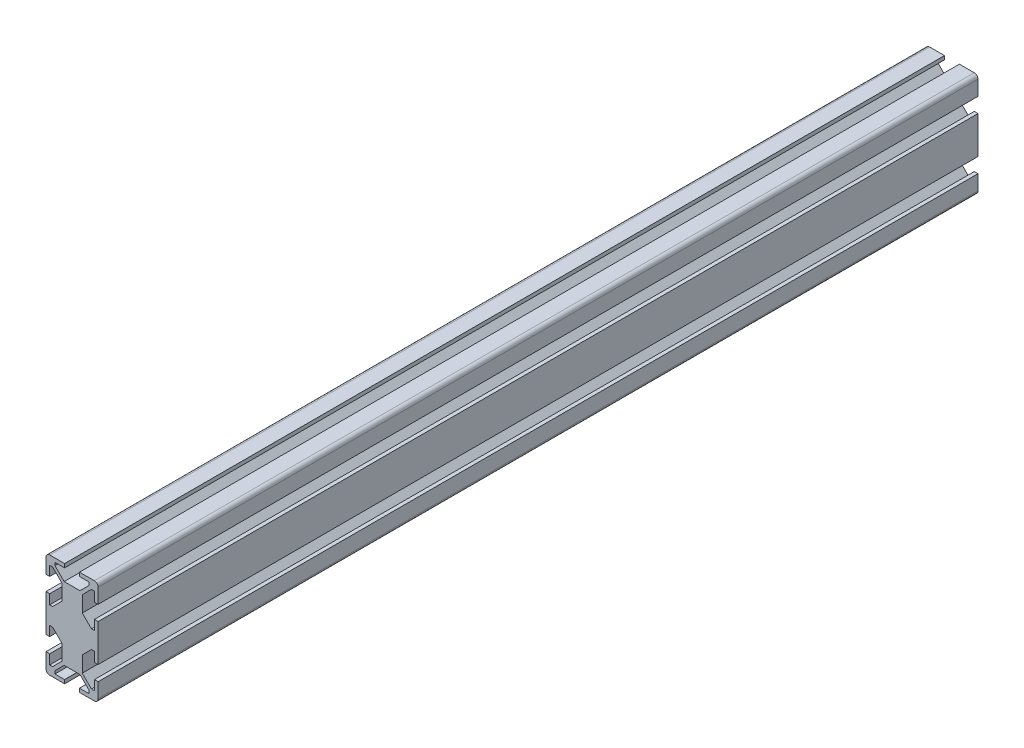
SolidWorks part; units mm, degrees
material "6061 Aluminum Alloy"
ref_plane "Front Plane" through (0, 0, 0) normal (0, 0, 1) x (1, 0, 0)
ref_plane "Top Plane" through (0, 0, 0) normal (0, 1, 0) x (1, 0, 0)
ref_plane "Right Plane" through (0, 0, 0) normal (1, 0, 0) x (0, 0, -1)
sketch "Sketch1" plane through (0, 0, 0) normal (0, 0, 1) x (1, 0, 0)
  line L0 (-51.9455, 19.536) -> (-51.9455, -0.464)
  line L1 (-51.9455, -0.464) -> (-49.9455, -0.464)
  line L2 (-49.9455, -0.464) -> (-49.9455, 4.7413)
  line L3 (-49.9455, 4.7413) -> (-48.3862, 4.7413)
  line L4 (-48.3862, 4.7413) -> (-43.4455, -0.1995)
  line L5 (-43.4455, -0.1995) -> (-43.4455, -8.7179)
  line L6 (-43.4455, -8.7179) -> (-48.3862, -13.6587)
  line L7 (-48.3862, -13.6587) -> (-49.9455, -13.6587)
  line L8 (-49.9455, -13.6587) -> (-49.9455, -8.4587)
  line L9 (-49.9455, -8.4587) -> (-51.9455, -8.4587)
  line L10 (-51.9455, -8.4587) -> (-51.9455, -16.4587)
  line L11 (-49.9455, -18.4587) -> (-41.9455, -18.4587)
  line L12 (-41.9455, -18.4587) -> (-41.9455, -16.4587)
  line L13 (-41.9455, -16.4587) -> (-47.1455, -16.4587)
  line L14 (-47.1455, -16.4587) -> (-47.1455, -14.8995)
  line L15 (-47.1455, -14.8995) -> (-42.2047, -9.9587)
  line L16 (-42.2047, -9.9587) -> (-33.6862, -9.9587)
  line L17 (-33.6862, -9.9587) -> (-28.7455, -14.8995)
  line L18 (-28.7455, -14.8995) -> (-28.7455, -16.4587)
  line L19 (-28.7455, -16.4587) -> (-33.9455, -16.4587)
  line L20 (-33.9455, -16.4587) -> (-33.9455, -18.4587)
  line L21 (-33.9455, -18.4587) -> (-25.9455, -18.4587)
  line L22 (-23.9455, -16.4587) -> (-23.9455, -8.4587)
  line L23 (-23.9455, -8.4587) -> (-25.9455, -8.4587)
  line L24 (-25.9455, -8.4587) -> (-25.9455, -13.6587)
  line L25 (-25.9455, -13.6587) -> (-27.5047, -13.6587)
  line L26 (-27.5047, -13.6587) -> (-32.4455, -8.7179)
  line L27 (-32.4455, -8.7179) -> (-32.4455, -0.1995)
  line L28 (-32.4455, -0.1995) -> (-27.5047, 4.7413)
  line L29 (-27.5047, 4.7413) -> (-25.9455, 4.7413)
  line L30 (-25.9455, 4.7413) -> (-25.9455, -0.464)
  line L31 (-25.9455, -0.464) -> (-23.9455, -0.464)
  line L32 (-23.9455, -0.464) -> (-23.9455, 19.5413)
  line L33 (-23.9455, 19.5413) -> (-25.9455, 19.5413)
  line L34 (-25.9455, 19.5413) -> (-25.9455, 14.3413)
  line L35 (-25.9455, 14.3413) -> (-27.5047, 14.3413)
  line L36 (-27.5047, 14.3413) -> (-32.4455, 19.2821)
  line L37 (-32.4455, 19.2821) -> (-32.4455, 27.8005)
  line L38 (-32.4455, 27.8005) -> (-27.5047, 32.7413)
  line L39 (-27.5047, 32.7413) -> (-25.9455, 32.7413)
  line L40 (-25.9455, 32.7413) -> (-25.9455, 27.5413)
  line L41 (-25.9455, 27.5413) -> (-23.9455, 27.5413)
  line L42 (-23.9455, 27.5413) -> (-23.9455, 35.5413)
  line L43 (-25.9455, 37.5413) -> (-33.9455, 37.5413)
  line L44 (-33.9455, 37.5413) -> (-33.9455, 35.5413)
  line L45 (-33.9455, 35.5413) -> (-28.7455, 35.5413)
  line L46 (-28.7455, 35.5413) -> (-28.7455, 33.9821)
  line L47 (-28.7455, 33.9821) -> (-33.6862, 29.0413)
  line L48 (-33.6862, 29.0413) -> (-42.2047, 29.0413)
  line L49 (-42.2047, 29.0413) -> (-47.1455, 33.9821)
  line L50 (-47.1455, 33.9821) -> (-47.1455, 35.5413)
  line L51 (-47.1455, 35.5413) -> (-41.9455, 35.5413)
  line L52 (-41.9455, 35.5413) -> (-41.9455, 37.5413)
  line L53 (-41.9455, 37.5413) -> (-49.9455, 37.5413)
  line L54 (-51.9455, 35.5413) -> (-51.9455, 27.5413)
  line L55 (-51.9455, 27.5413) -> (-49.9455, 27.5413)
  line L56 (-49.9455, 27.5413) -> (-49.9455, 32.736)
  line L57 (-49.9455, 32.736) -> (-48.3721, 32.736)
  line L58 (-48.3721, 32.736) -> (-43.4313, 27.7953)
  line L59 (-43.4313, 27.7953) -> (-43.4313, 19.2768)
  line L60 (-43.4313, 19.2768) -> (-48.3721, 14.336)
  line L61 (-48.3721, 14.336) -> (-49.9313, 14.336)
  line L62 (-49.9313, 14.336) -> (-49.9313, 19.536)
  line L63 (-49.9313, 19.536) -> (-51.9455, 19.536)
  line L64 (-33.6862, 18.0413) -> (-42.2047, 18.0413)
  line L65 (-42.2047, 18.0413) -> (-47.1455, 13.1005)
  line L66 (-47.1455, 13.1005) -> (-47.1455, 5.9821)
  line L67 (-47.1455, 5.9821) -> (-42.2047, 1.0413)
  line L68 (-42.2047, 1.0413) -> (-33.6862, 1.0413)
  line L69 (-33.6862, 1.0413) -> (-28.7455, 5.9821)
  line L70 (-28.7455, 5.9821) -> (-28.7455, 13.1005)
  line L71 (-28.7455, 13.1005) -> (-33.6862, 18.0413)
  arc A0 (-51.9455, -16.4587) -> (-49.9455, -18.4587) centre (-49.9455, -16.4587) ccw
  arc A1 (-25.9455, -18.4587) -> (-23.9455, -16.4587) centre (-25.9455, -16.4587) ccw
  arc A2 (-23.9455, 35.5413) -> (-25.9455, 37.5413) centre (-25.9455, 35.5413) ccw
  arc A3 (-49.9455, 37.5413) -> (-51.9455, 35.5413) centre (-49.9455, 35.5413) ccw
  circle A4 centre (-37.9455, -4.4587) radius 3.25
  circle A5 centre (-37.9455, 23.5413) radius 3.25
extrude "Extrusion2" add sketch "Sketch1" along normal up to vertex (161.5 mm away) and the other way up to vertex (161.5 mm away) contours L53 A3 L54 L55 L56 L57 L58 L59 L60 L61 L62 L63 L0 L1 L2 L3 L4 L5 L6 L7 L8 L9 L10 A0 L11 L12 L13 L14 L15 L16 L17 L18 L19 L20 L21 A1 L22 L23 L24 L25 L26 L27 L28 L29 L30 L31 L32 L33 L34 L35 L36
hole_wizard "Ø4.7 (4.7) Diameter Hole1" positions "Sketch3" profile "Sketch4" hole size "Ø4.7" standard "Macron Ansi Metric" end condition through all
sketch "Sketch3" plane through (-23.9455, 0, 0) normal (1, 0, 0) x (0, 0, -1)
  line L0 (-161.5, -0.464) -> (-161.5, 19.5413) construction
  line L1 (-161.5, 37.5413) -> (161.5, 37.5413) construction
  point P0 (-140.5, 23.5413)
  point P1 (140.5, 23.5413)
  dimension "D1" = 21
  dimension "D2" = 14
  dimension "D3" = 21
sketch "Sketch4" plane through (-23.9455, 23.5413, 140.5) normal (0, 1, 0) x (0, 0, -1)
  line L0 (0, 0) -> (0, 28)
  line L1 (0, 28) -> (2.375, 28)
  line L2 (2.375, 28) -> (2.375, 0)
  line L5 (2.375, 0) -> (0, 0)
  line L11 (0, -6.35) -> (0, 107.95) construction
  dimension "Thru Hole Dia." = 4.75
  dimension "Thru Hole Depth" = 28
sketch "Sketch5" plane through (0, 0, 161.5) normal (0, 0, 1) x (1, 0, 0)
  line L64 (-41.9455, 37.5413) -> (-49.9455, 37.5413)
  line L65 (-51.9455, 35.5413) -> (-51.9455, 27.5413)
  line L66 (-51.9455, 27.5413) -> (-49.9455, 27.5413)
  line L67 (-49.9455, 27.5413) -> (-49.9455, 32.736)
  line L68 (-49.9455, 32.736) -> (-48.3721, 32.736)
  line L69 (-48.3721, 32.736) -> (-43.4313, 27.7953)
  line L70 (-43.4313, 27.7953) -> (-43.4313, 19.2768)
  line L71 (-43.4313, 19.2768) -> (-48.3721, 14.336)
  line L72 (-48.3721, 14.336) -> (-49.9313, 14.336)
  line L73 (-49.9313, 14.336) -> (-49.9313, 19.536)
  line L74 (-49.9313, 19.536) -> (-51.9455, 19.536)
  line L75 (-51.9455, 19.536) -> (-51.9455, -0.464)
  line L76 (-51.9455, -0.464) -> (-49.9455, -0.464)
  line L77 (-49.9455, -0.464) -> (-49.9455, 4.7413)
  line L78 (-49.9455, 4.7413) -> (-48.3862, 4.7413)
  line L79 (-48.3862, 4.7413) -> (-43.4455, -0.1995)
  line L80 (-43.4455, -0.1995) -> (-43.4455, -8.7179)
  line L81 (-43.4455, -8.7179) -> (-48.3862, -13.6587)
  line L82 (-48.3862, -13.6587) -> (-49.9455, -13.6587)
  line L83 (-49.9455, -13.6587) -> (-49.9455, -8.4587)
  line L84 (-49.9455, -8.4587) -> (-51.9455, -8.4587)
  line L85 (-51.9455, -8.4587) -> (-51.9455, -16.4587)
  line L86 (-49.9455, -18.4587) -> (-41.9455, -18.4587)
  line L87 (-41.9455, -18.4587) -> (-41.9455, -16.4587)
  line L88 (-41.9455, -16.4587) -> (-47.1455, -16.4587)
  line L89 (-47.1455, -16.4587) -> (-47.1455, -14.8995)
  line L90 (-47.1455, -14.8995) -> (-42.2047, -9.9587)
  line L91 (-42.2047, -9.9587) -> (-33.6862, -9.9587)
  line L92 (-33.6862, -9.9587) -> (-28.7455, -14.8995)
  line L93 (-28.7455, -14.8995) -> (-28.7455, -16.4587)
  line L94 (-28.7455, -16.4587) -> (-33.9455, -16.4587)
  line L95 (-33.9455, -16.4587) -> (-33.9455, -18.4587)
  line L96 (-33.9455, -18.4587) -> (-25.9455, -18.4587)
  line L97 (-23.9455, -16.4587) -> (-23.9455, -8.4587)
  line L98 (-23.9455, -8.4587) -> (-25.9455, -8.4587)
  line L99 (-25.9455, -8.4587) -> (-25.9455, -13.6587)
  line L100 (-25.9455, -13.6587) -> (-27.5047, -13.6587)
  line L101 (-27.5047, -13.6587) -> (-32.4455, -8.7179)
  line L102 (-32.4455, -8.7179) -> (-32.4455, -0.1995)
  line L103 (-32.4455, -0.1995) -> (-27.5047, 4.7413)
  line L104 (-27.5047, 4.7413) -> (-25.9455, 4.7413)
  line L105 (-25.9455, 4.7413) -> (-25.9455, -0.464)
  line L106 (-25.9455, -0.464) -> (-23.9455, -0.464)
  line L107 (-23.9455, -0.464) -> (-23.9455, 19.5413)
  line L108 (-23.9455, 19.5413) -> (-25.9455, 19.5413)
  line L109 (-25.9455, 19.5413) -> (-25.9455, 14.3413)
  line L110 (-25.9455, 14.3413) -> (-27.5047, 14.3413)
  line L111 (-27.5047, 14.3413) -> (-32.4455, 19.2821)
  line L112 (-32.4455, 19.2821) -> (-32.4455, 27.8005)
  line L113 (-32.4455, 27.8005) -> (-27.5047, 32.7413)
  line L114 (-27.5047, 32.7413) -> (-25.9455, 32.7413)
  line L115 (-25.9455, 32.7413) -> (-25.9455, 27.5413)
  line L116 (-25.9455, 27.5413) -> (-23.9455, 27.5413)
  line L117 (-23.9455, 27.5413) -> (-23.9455, 35.5413)
  line L118 (-25.9455, 37.5413) -> (-33.9455, 37.5413)
  line L119 (-33.9455, 37.5413) -> (-33.9455, 35.5413)
  line L120 (-33.9455, 35.5413) -> (-28.7455, 35.5413)
  line L121 (-28.7455, 35.5413) -> (-28.7455, 33.9821)
  line L122 (-28.7455, 33.9821) -> (-33.6862, 29.0413)
  line L123 (-33.6862, 29.0413) -> (-42.2047, 29.0413)
  line L124 (-42.2047, 29.0413) -> (-47.1455, 33.9821)
  line L125 (-47.1455, 33.9821) -> (-47.1455, 35.5413)
  line L126 (-47.1455, 35.5413) -> (-41.9455, 35.5413)
  line L127 (-41.9455, 35.5413) -> (-41.9455, 37.5413)
  line L128 (-41.9455, 37.5413) -> (-49.9455, 37.5413)
  line L129 (-51.9455, 35.5413) -> (-51.9455, 27.5413)
  line L130 (-51.9455, 27.5413) -> (-49.9455, 27.5413)
  line L131 (-49.9455, 27.5413) -> (-49.9455, 32.736)
  line L132 (-49.9455, 32.736) -> (-48.3721, 32.736)
  line L133 (-48.3721, 32.736) -> (-43.4313, 27.7953)
  line L134 (-43.4313, 27.7953) -> (-43.4313, 19.2768)
  line L135 (-43.4313, 19.2768) -> (-48.3721, 14.336)
  line L136 (-48.3721, 14.336) -> (-49.9313, 14.336)
  line L137 (-49.9313, 14.336) -> (-49.9313, 19.536)
  line L138 (-49.9313, 19.536) -> (-51.9455, 19.536)
  line L139 (-51.9455, 19.536) -> (-51.9455, -0.464)
  line L140 (-51.9455, -0.464) -> (-49.9455, -0.464)
  line L141 (-49.9455, -0.464) -> (-49.9455, 4.7413)
  line L142 (-49.9455, 4.7413) -> (-48.3862, 4.7413)
  line L143 (-48.3862, 4.7413) -> (-43.4455, -0.1995)
  line L144 (-43.4455, -0.1995) -> (-43.4455, -8.7179)
  line L145 (-43.4455, -8.7179) -> (-48.3862, -13.6587)
  line L146 (-48.3862, -13.6587) -> (-49.9455, -13.6587)
  line L147 (-49.9455, -13.6587) -> (-49.9455, -8.4587)
  line L148 (-49.9455, -8.4587) -> (-51.9455, -8.4587)
  line L149 (-51.9455, -8.4587) -> (-51.9455, -16.4587)
  line L150 (-49.9455, -18.4587) -> (-41.9455, -18.4587)
  line L151 (-41.9455, -18.4587) -> (-41.9455, -16.4587)
  line L152 (-41.9455, -16.4587) -> (-47.1455, -16.4587)
  line L153 (-47.1455, -16.4587) -> (-47.1455, -14.8995)
  line L154 (-47.1455, -14.8995) -> (-42.2047, -9.9587)
  line L155 (-42.2047, -9.9587) -> (-33.6862, -9.9587)
  line L156 (-33.6862, -9.9587) -> (-28.7455, -14.8995)
  line L157 (-28.7455, -14.8995) -> (-28.7455, -16.4587)
  line L158 (-28.7455, -16.4587) -> (-33.9455, -16.4587)
  line L159 (-33.9455, -16.4587) -> (-33.9455, -18.4587)
  line L160 (-33.9455, -18.4587) -> (-25.9455, -18.4587)
  line L161 (-23.9455, -16.4587) -> (-23.9455, -8.4587)
  line L162 (-23.9455, -8.4587) -> (-25.9455, -8.4587)
  line L163 (-25.9455, -8.4587) -> (-25.9455, -13.6587)
  line L164 (-25.9455, -13.6587) -> (-27.5047, -13.6587)
  line L165 (-27.5047, -13.6587) -> (-32.4455, -8.7179)
  line L166 (-32.4455, -8.7179) -> (-32.4455, -0.1995)
  line L167 (-32.4455, -0.1995) -> (-27.5047, 4.7413)
  line L168 (-27.5047, 4.7413) -> (-25.9455, 4.7413)
  line L169 (-25.9455, 4.7413) -> (-25.9455, -0.464)
  line L170 (-25.9455, -0.464) -> (-23.9455, -0.464)
  line L171 (-23.9455, -0.464) -> (-23.9455, 19.5413)
  line L172 (-23.9455, 19.5413) -> (-25.9455, 19.5413)
  line L173 (-25.9455, 19.5413) -> (-25.9455, 14.3413)
  line L174 (-25.9455, 14.3413) -> (-27.5047, 14.3413)
  line L175 (-27.5047, 14.3413) -> (-32.4455, 19.2821)
  line L176 (-32.4455, 19.2821) -> (-32.4455, 27.8005)
  line L177 (-32.4455, 27.8005) -> (-27.5047, 32.7413)
  line L178 (-27.5047, 32.7413) -> (-25.9455, 32.7413)
  line L179 (-25.9455, 32.7413) -> (-25.9455, 27.5413)
  line L180 (-25.9455, 27.5413) -> (-23.9455, 27.5413)
  line L181 (-23.9455, 27.5413) -> (-23.9455, 35.5413)
  line L182 (-25.9455, 37.5413) -> (-33.9455, 37.5413)
  line L183 (-33.9455, 37.5413) -> (-33.9455, 35.5413)
  line L184 (-33.9455, 35.5413) -> (-28.7455, 35.5413)
  line L185 (-28.7455, 35.5413) -> (-28.7455, 33.9821)
  line L186 (-28.7455, 33.9821) -> (-33.6862, 29.0413)
  line L187 (-33.6862, 29.0413) -> (-42.2047, 29.0413)
  line L188 (-42.2047, 29.0413) -> (-47.1455, 33.9821)
  line L189 (-47.1455, 33.9821) -> (-47.1455, 35.5413)
  line L190 (-47.1455, 35.5413) -> (-41.9455, 35.5413)
  line L191 (-41.9455, 35.5413) -> (-41.9455, 37.5413)
  arc A4 (-49.9455, 37.5413) -> (-51.9455, 35.5413) centre (-49.9455, 35.5413) ccw
  arc A5 (-51.9455, -16.4587) -> (-49.9455, -18.4587) centre (-49.9455, -16.4587) ccw
  arc A6 (-25.9455, -18.4587) -> (-23.9455, -16.4587) centre (-25.9455, -16.4587) ccw
  arc A7 (-23.9455, 35.5413) -> (-25.9455, 37.5413) centre (-25.9455, 35.5413) ccw
  arc A8 (-49.9455, 37.5413) -> (-51.9455, 35.5413) centre (-49.9455, 35.5413) ccw
  arc A9 (-51.9455, -16.4587) -> (-49.9455, -18.4587) centre (-49.9455, -16.4587) ccw
  arc A10 (-25.9455, -18.4587) -> (-23.9455, -16.4587) centre (-25.9455, -16.4587) ccw
  arc A11 (-23.9455, 35.5413) -> (-25.9455, 37.5413) centre (-25.9455, 35.5413) ccw
  dimension "D1" = 0
extrude "Boss-Extrude1" add sketch "Sketch5" along normal blind 150
sketch "Sketch6" plane through (0, 0, 311.5) normal (0, 0, 1) x (1, 0, 0)
  line L0 (-23.9455, 9.5387) -> (-51.9455, 9.536)
  line L1 (-23.9455, -0.464) -> (-23.9455, 19.5413) construction
  line L2 (-51.9455, 19.536) -> (-51.9455, -0.464) construction
  line L3 (-37.9455, 29.0413) -> (-37.9455, -9.9587)
  line L4 (-33.6862, 29.0413) -> (-42.2047, 29.0413) construction
  line L5 (-42.2047, -9.9587) -> (-33.6862, -9.9587) construction
  point P12 (-37.9455, 9.5373)
